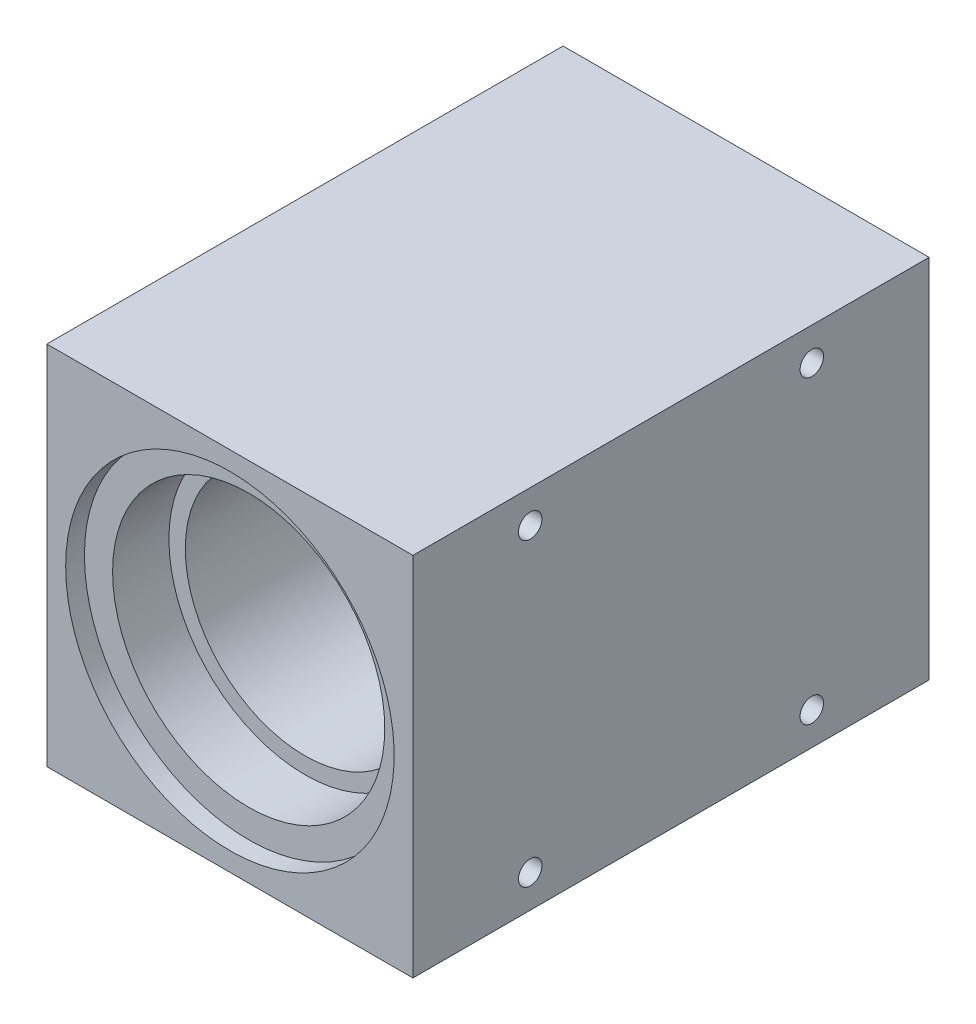
SolidWorks part; units mm, degrees
material "PLA Density Only"
ref_plane "Front Plane" through (0, 0, 0) normal (0, 0, 1) x (1, 0, 0)
ref_plane "Top Plane" through (0, 0, 0) normal (0, 1, 0) x (1, 0, 0)
ref_plane "Right Plane" through (0, 0, 0) normal (1, 0, 0) x (0, 0, -1)
sketch "Sketch1" plane through (0, 0, 0) normal (0, 0, 1) x (1, 0, 0)
  line L1 (-39, 39) -> (39, 39)
  line L2 (-39, 39) -> (-39, -39)
  line L3 (-39, -39) -> (39, -39)
  line L4 (39, 39) -> (39, -39)
  line L5 (-39, 39) -> (39, -39) construction
  line L6 (-39, -39) -> (39, 39) construction
  circle A0 centre (0, 0) radius 25.5
  point P0 (0, 0)
  dimension "D2" = 51
  dimension "D1" = 78
  dimension "D3" = 78
extrude "Boss-Extrude1" add sketch "Sketch1" along normal blind 110
sketch "Sketch2" plane through (0, 0, 0) normal (0, 0, -1) x (-1, 0, 0)
  circle A0 centre (0, 0) radius 29
  dimension "D1" = 58
extrude "Cut-Extrude1" cut sketch "Sketch2" against normal blind 12 from offset 4 offset against normal yes
sketch "Sketch3" plane through (0, 0, 110) normal (0, 0, 1) x (1, 0, 0)
  circle A0 centre (0, 0) radius 29
  dimension "D1" = 58
extrude "Cut-Extrude2" cut sketch "Sketch3" against normal blind 12 from offset 4 offset against normal yes
sketch "Thrust AX4565" plane through (0, 0, 0) normal (0, 0, 1) x (1, 0, 0)
  circle A0 centre (0, 0) radius 35
  circle A1 centre (0, 0) radius 25
  dimension "D1" = 70
  dimension "D2" = 50
extrude "Cut-Extrude6" cut sketch "Thrust AX4565" along normal blind 4
sketch "Sketch13" plane through (0, 0, 110) normal (0, 0, -1) x (-1, 0, 0)
  circle A0 centre (0, 0) radius 35
  circle A1 centre (0, 0) radius 25
  dimension "D1" = 70
  dimension "D2" = 50
extrude "Cut-Extrude7" cut sketch "Sketch13" along normal blind 4
sketch "Sketch8" plane through (39, 0, 0) normal (1, 0, 0) x (0, 0, -1)
  line L0 (-110, 39) -> (0, 39) construction
  line L1 (-110, -39) -> (-110, 39) construction
  line L2 (-110, -39) -> (0, -39) construction
  line L3 (0, -39) -> (0, 39) construction
  circle A0 centre (-85, 32) radius 2.5
  circle A1 centre (-25, 32) radius 2.5
  circle A2 centre (-25, -32) radius 2.5
  circle A3 centre (-85, -32) radius 2.5
  dimension "D1" = 5
  dimension "D2" = 5
  dimension "D3" = 5
  dimension "D4" = 5
  dimension "D5" = 7
  dimension "D6" = 25
  dimension "D7" = 7
  dimension "D8" = 25
extrude "Cut-Extrude3" cut sketch "Sketch8" against normal through all
sketch "Sketch12" plane through (0, 39, 0) normal (0, -1, 0) x (1, 0, 0)
  line L0 (0, 0) -> (0, 114.0796) construction
  line L1 (-39, 110) -> (39, 110) construction
  circle A4 centre (14.9, 102) radius 1.5
  circle A6 centre (14.9, 90) radius 1.5
  circle A10 centre (-14.9, 102) radius 1.5
  circle A11 centre (-14.9, 90) radius 1.5
  dimension "D1" = 3
  dimension "D2" = 12
  dimension "D3" = 3
  dimension "D6" = 14.9
  dimension "D7" = 8
extrude "Cut-Extrude5" [suppressed] cut sketch "Sketch12" along normal blind 5
sketch "Sketch15" plane through (0, 0, 0) normal (1, 0, 0) x (0, 0, -1)
  line L0 (-92.8462, 33.2027) -> (-87.3462, 33.2027)
  line L1 (-104.8719, 32.4134) -> (-99.3719, 32.4134)
  line L2 (-104.8719, 32.4134) -> (-104.8719, 29.9134)
  line L3 (-104.8719, 29.9134) -> (-99.3719, 29.9134)
  line L4 (-99.3719, 32.4134) -> (-99.3719, 29.9134)
  line L5 (-104.8719, 32.4134) -> (-99.3719, 29.9134) construction
  line L6 (-104.8719, 29.9134) -> (-99.3719, 32.4134) construction
  line L7 (-92.8462, 33.2027) -> (-92.8462, 30.7027)
  line L8 (-92.8462, 30.7027) -> (-87.3462, 30.7027)
  line L9 (-87.3462, 33.2027) -> (-87.3462, 30.7027)
  point P0 (-102.1219, 31.1634)
  dimension "D1" = 2.5
  dimension "D2" = 5.5
equation "\"th_depth\"= 100"
equation "\"tube_OD\"=45"
equation "\"tube_housing_length\"=80"
